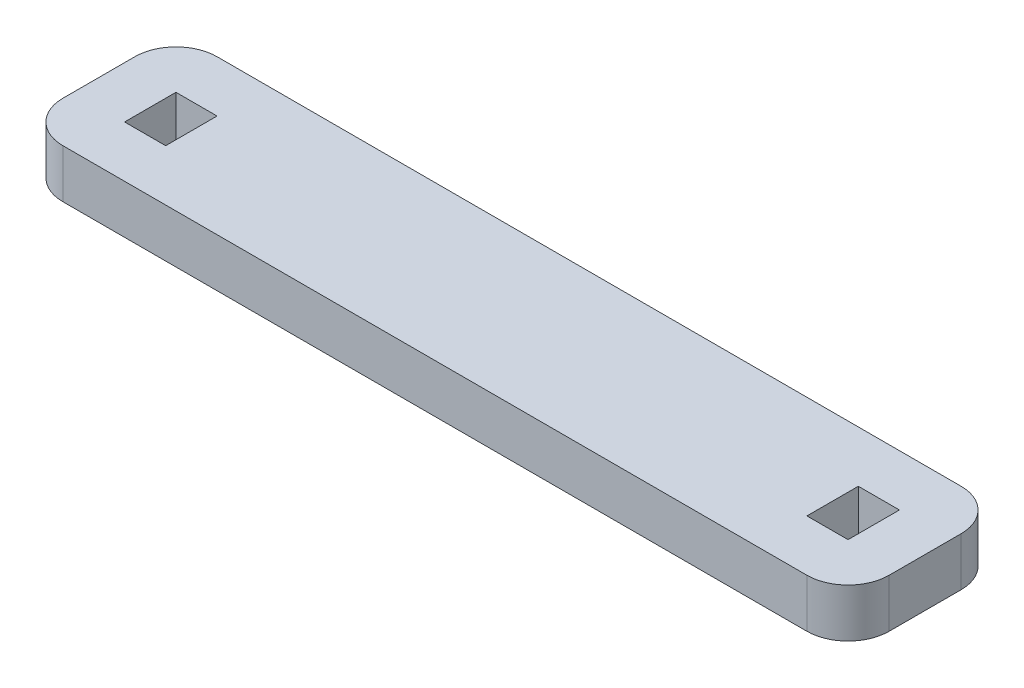
SolidWorks part; units mm, degrees
ref_plane "Front Plane" through (0, 0, 0) normal (0, 0, 1) x (1, 0, 0)
ref_plane "Top Plane" through (0, 0, 0) normal (0, 1, 0) x (1, 0, 0)
ref_plane "Right Plane" through (0, 0, 0) normal (1, 0, 0) x (0, 0, -1)
sketch "Sketch1" plane through (0, 0, 0) normal (0, 1, 0) x (1, 0, 0)
  line L0 (-21.082, 0) -> (21.082, 0) construction
  line L6 (25.527, -4.7625) -> (-25.527, -4.7625)
  line L7 (-19.812, -1.5875) -> (-22.352, -1.5875)
  line L8 (-19.812, -1.5875) -> (-19.812, 1.5875)
  line L9 (-19.812, 1.5875) -> (-22.352, 1.5875)
  line L10 (-22.352, -1.5875) -> (-22.352, 1.5875)
  line L11 (-19.812, -1.5875) -> (-22.352, 1.5875) construction
  line L12 (-19.812, 1.5875) -> (-22.352, -1.5875) construction
  line L13 (22.352, -1.5875) -> (19.812, -1.5875)
  line L14 (22.352, -1.5875) -> (22.352, 1.5875)
  line L15 (22.352, 1.5875) -> (19.812, 1.5875)
  line L16 (19.812, -1.5875) -> (19.812, 1.5875)
  line L17 (22.352, -1.5875) -> (19.812, 1.5875) construction
  line L18 (22.352, 1.5875) -> (19.812, -1.5875) construction
  line L19 (25.527, -4.7625) -> (25.527, 4.7625)
  line L20 (25.527, 4.7625) -> (-25.527, 4.7625)
  line L21 (-25.527, -4.7625) -> (-25.527, 4.7625)
  line L22 (25.527, -4.7625) -> (-25.527, 4.7625) construction
  line L23 (25.527, 4.7625) -> (-25.527, -4.7625) construction
  point P0 (0, 0)
  point P1 (0, 0)
  point P6 (-21.082, 0)
  point P11 (21.082, 0)
  dimension "D1" = 9.525
  dimension "D2" = 3.175
  dimension "D3" = 2.54
  dimension "D4" = 42.164
  dimension "D5" = 3.175
extrude "Boss-Extrude1" add sketch "Sketch1" along normal mid plane 3
fillet "Fillet1" radius 2.54 4 edges at (-25.527, 0, -4.7625) (25.527, 0, -4.7625) (25.527, 0, 4.7625) (-25.527, 0, 4.7625)
